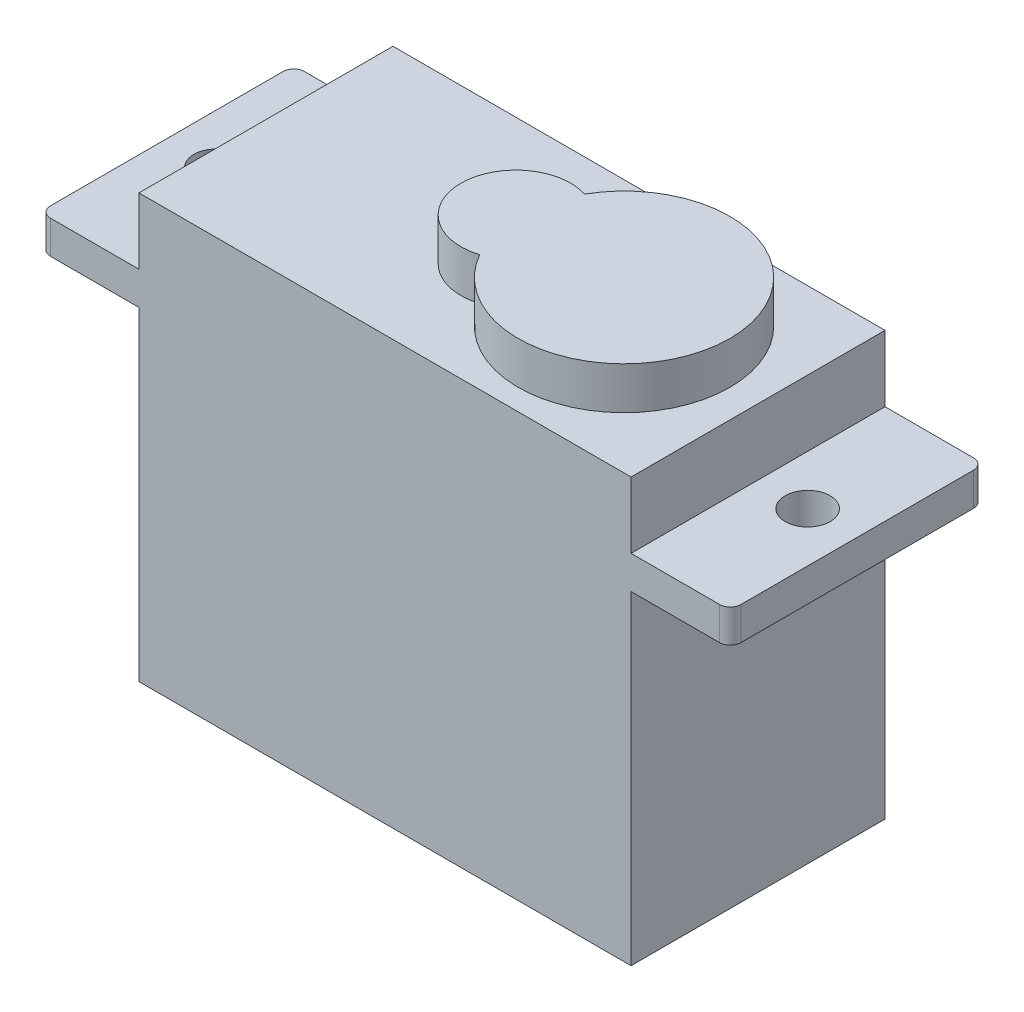
SolidWorks part; units mm, degrees
ref_plane "Front" through (0, 0, 0) normal (0, 0, 1) x (1, 0, 0)
ref_plane "Top" through (0, 0, 0) normal (0, 1, 0) x (1, 0, 0)
ref_plane "Right" through (0, 0, 0) normal (1, 0, 0) x (0, 0, -1)
sketch "Sketch1" plane through (0, 0, 0) normal (0, 1, 0) x (1, 0, 0)
  line L1 (-11.811, 6.096) -> (11.811, 6.096)
  line L2 (-11.811, 6.096) -> (-11.811, -6.096)
  line L3 (-11.811, -6.096) -> (11.811, -6.096)
  line L4 (11.811, 6.096) -> (11.811, -6.096)
  line L5 (-11.811, 6.096) -> (11.811, -6.096) construction
  line L6 (-11.811, -6.096) -> (11.811, 6.096) construction
  point P0 (0, 0)
  dimension "D1" = 12.192
  dimension "D2" = 23.622
extrude "Boss-Extrude1" add sketch "Sketch1" along normal blind 20.32
sketch "Sketch2" plane through (0, 20.32, 0) normal (0, 1, 0) x (1, 0, 0)
  line L0 (-55, 0) -> (55, 0) construction
  circle A0 centre (5.3787, 0) radius 5.0807
  arc A1 (0.9669, 2.5199) -> (0.9669, -2.5199) centre (0.1842, 0) ccw
extrude "Boss-Extrude2" add sketch "Sketch2" along normal blind 2.032 contours A0 | A0 A1
sketch "Sketch3" plane through (11.811, 0, 0) normal (1, 0, 0) x (0, 0, -1)
  line L0 (-6.096, 20.32) -> (-6.096, 0) construction
  line L1 (-6.096, 17.145) -> (6.096, 17.145)
  line L2 (-6.096, 17.145) -> (-6.096, 15.5575)
  line L3 (-6.096, 15.5575) -> (6.096, 15.5575)
  line L4 (6.096, 17.145) -> (6.096, 15.5575)
  line L5 (6.096, 20.32) -> (6.096, 0) construction
  line L6 (5.0807, 20.32) -> (-5.0807, 20.32) construction
  dimension "D1" = 3.175
  dimension "D2" = 1.5875
extrude "Boss-Extrude3" add sketch "Sketch3" along normal blind 4.7625
sketch "Sketch5" plane through (0, 17.145, 0) normal (0, 1, 0) x (1, 0, 0)
  line L0 (-55, 0) -> (55, 0) construction
  line L1 (16.5735, 6.096) -> (11.811, 6.096) construction
  circle A0 centre (14.1922, 0) radius 1.0795
  point P6 (14.1922, 6.096)
  dimension "D1" = 2.159
extrude "Cut-Extrude1" cut sketch "Sketch5" against normal up to next
mirror "Mirror1" about plane through (0, 0, 0) normal (1, 0, 0) of "Cut-Extrude1", "Boss-Extrude3"
fillet "Fillet1" radius 0.508 4 edges at (16.5735, 16.3513, 6.096) (16.5735, 16.3513, -6.096) (-16.5735, 16.3513, 6.096) (-16.5735, 16.3513, -6.096)
